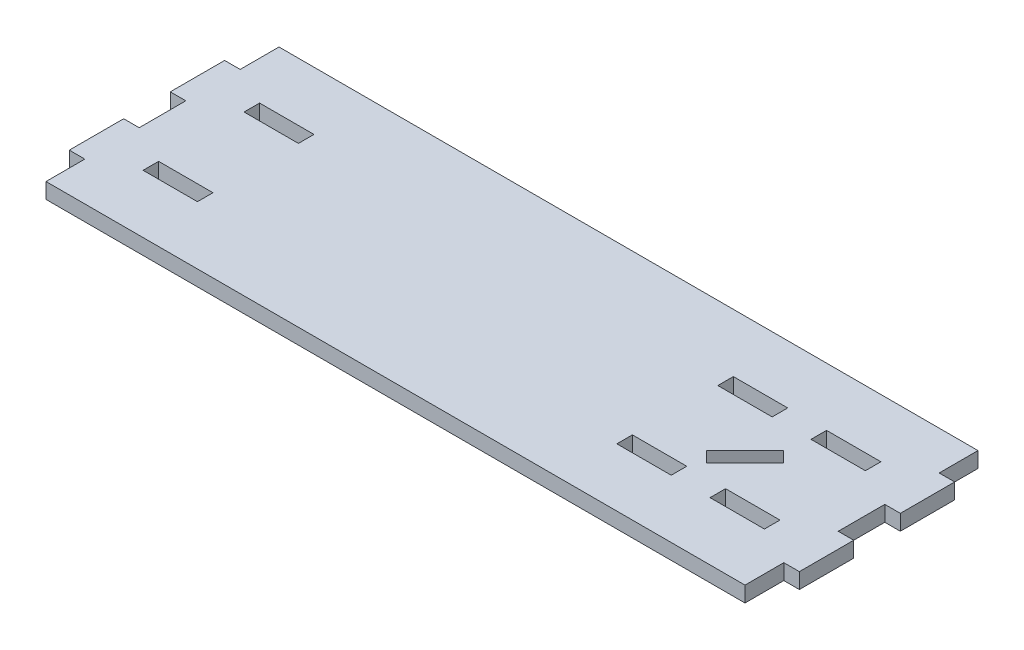
SolidWorks part; units mm, degrees
ref_plane "Front Plane" through (0, 0, 0) normal (0, 0, 1) x (1, 0, 0)
ref_plane "Top Plane" through (0, 0, 0) normal (0, 1, 0) x (1, 0, 0)
ref_plane "Right Plane" through (0, 0, 0) normal (1, 0, 0) x (0, 0, -1)
sketch "Sketch1" plane through (0, 0, 0) normal (0, 1, 0) x (1, 0, 0)
  line L1 (-23.0501, 13.8238) -> (66.9499, 13.8238)
  line L2 (-23.0501, 13.8238) -> (-23.0501, -16.1762)
  line L3 (-23.0501, -16.1762) -> (66.9499, -16.1762)
  line L4 (66.9499, 13.8238) -> (66.9499, -16.1762)
  line L5 (55.8399, -0.1143) -> (50.8902, -5.0641)
  line L6 (55.8399, -0.1143) -> (54.4257, 1.2999)
  line L7 (50.8902, -5.0641) -> (49.4759, -3.6498)
  line L8 (54.4257, 1.2999) -> (49.4759, -3.6498)
  line L9 (-23.0501, -11.1762) -> (-25.0501, -11.1762)
  line L10 (-23.0501, -11.1762) -> (-23.0501, -4.1762)
  line L11 (-23.0501, -4.1762) -> (-25.0501, -4.1762)
  line L12 (-25.0501, -11.1762) -> (-25.0501, -4.1762)
  line L13 (-23.0501, 1.8238) -> (-25.0501, 1.8238)
  line L14 (-23.0501, 1.8238) -> (-23.0501, 8.8238)
  line L15 (-23.0501, 8.8238) -> (-25.0501, 8.8238)
  line L16 (-25.0501, 1.8238) -> (-25.0501, 8.8238)
  line L17 (66.9499, -11.1762) -> (68.9499, -11.1762)
  line L18 (66.9499, -11.1762) -> (66.9499, -4.1762)
  line L19 (66.9499, -4.1762) -> (68.9499, -4.1762)
  line L20 (68.9499, -11.1762) -> (68.9499, -4.1762)
  line L21 (66.9499, 1.8238) -> (68.9499, 1.8238)
  line L22 (66.9499, 1.8238) -> (66.9499, 8.8238)
  line L23 (66.9499, 8.8238) -> (68.9499, 8.8238)
  line L24 (68.9499, 1.8238) -> (68.9499, 8.8238)
  line L25 (61.9499, 6.3238) -> (54.9499, 6.3238)
  line L26 (61.9499, 6.3238) -> (61.9499, 4.3238)
  line L27 (61.9499, 4.3238) -> (54.9499, 4.3238)
  line L28 (54.9499, 6.3238) -> (54.9499, 4.3238)
  line L29 (54.9499, -6.6762) -> (61.9499, -6.6762)
  line L30 (54.9499, -6.6762) -> (54.9499, -8.6762)
  line L31 (54.9499, -8.6762) -> (61.9499, -8.6762)
  line L32 (61.9499, -6.6762) -> (61.9499, -8.6762)
  line L33 (42.9499, 6.3238) -> (49.9499, 6.3238)
  line L34 (42.9499, 6.3238) -> (42.9499, 4.3238)
  line L35 (42.9499, 4.3238) -> (49.9499, 4.3238)
  line L36 (49.9499, 6.3238) -> (49.9499, 4.3238)
  line L37 (42.9499, -6.6762) -> (49.9499, -6.6762)
  line L38 (42.9499, -6.6762) -> (42.9499, -8.6762)
  line L39 (42.9499, -8.6762) -> (49.9499, -8.6762)
  line L40 (49.9499, -6.6762) -> (49.9499, -8.6762)
  line L41 (-18.0501, 6.3238) -> (-11.0501, 6.3238)
  line L42 (-18.0501, 6.3238) -> (-18.0501, 4.3238)
  line L43 (-18.0501, 4.3238) -> (-11.0501, 4.3238)
  line L44 (-11.0501, 6.3238) -> (-11.0501, 4.3238)
  line L45 (-18.0501, -6.6762) -> (-11.0501, -6.6762)
  line L46 (-18.0501, -6.6762) -> (-18.0501, -8.6762)
  line L47 (-18.0501, -8.6762) -> (-11.0501, -8.6762)
  line L48 (-11.0501, -6.6762) -> (-11.0501, -8.6762)
  dimension "D24" = 11.11
  dimension "D4" = 90
  dimension "D5" = 30
  dimension "D6" = 45
  dimension "D7" = 7
  dimension "D8" = 2
  dimension "D9" = 7
  dimension "D10" = 7
  dimension "D11" = 2
  dimension "D12" = 5
  dimension "D13" = 5
  dimension "D14" = 2
  dimension "D15" = 2
  dimension "D16" = 7
  dimension "D17" = 7
  dimension "D18" = 5
  dimension "D19" = 5
  dimension "D20" = 6
  dimension "D21" = 6
  dimension "D22" = 2
  dimension "D23" = 11.1121
  dimension "D26" = 7
  dimension "D27" = 7
  dimension "D28" = 2
  dimension "D29" = 2
  dimension "D30" = 7
  dimension "D31" = 7
  dimension "D32" = 7
  dimension "D33" = 7
  dimension "D34" = 2
  dimension "D35" = 2
  dimension "D36" = 2
  dimension "D37" = 2
  dimension "D38" = 5
  dimension "D39" = 5
  dimension "D40" = 5
  dimension "D41" = 5
  dimension "D42" = 5
  dimension "D43" = 5
  dimension "D44" = 7.5
  dimension "D45" = 11
  dimension "D46" = 7.5
  dimension "D47" = 2.5
  dimension "D48" = 2.5
  dimension "D49" = 2.5
  dimension "D50" = 2.5
  dimension "D51" = 7.5
  dimension "D52" = 11
  dimension "D53" = 7.5
  dimension "D54" = 7.5
  dimension "D55" = 11
  dimension "D56" = 7.5
extrude "Boss-Extrude1" add sketch "Sketch1" along normal blind 2
